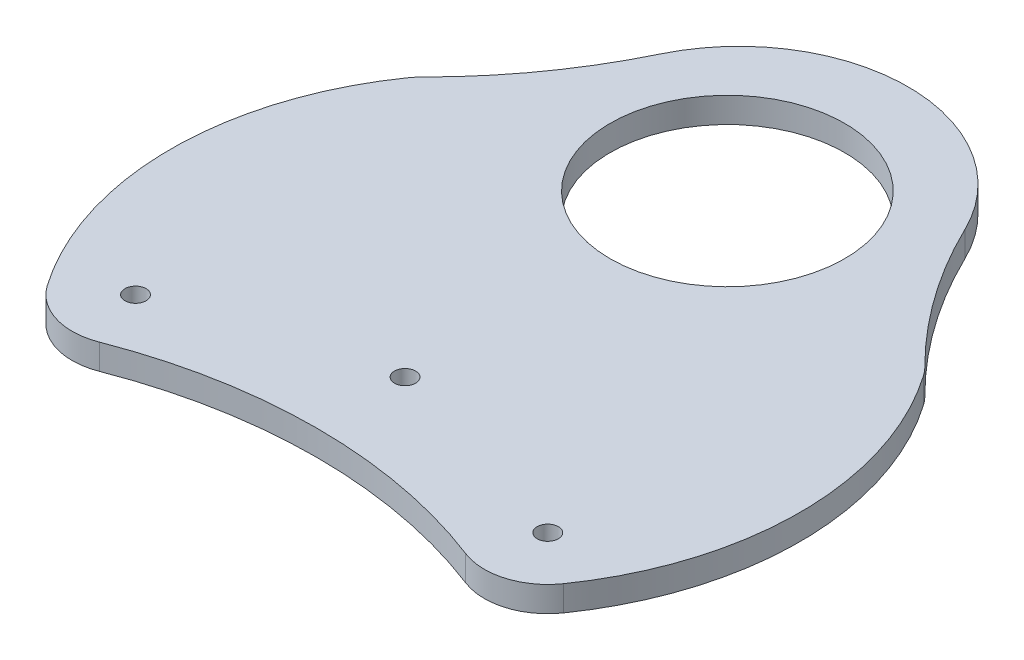
SolidWorks part; units mm, degrees
ref_plane "Front Plane" through (0, 0, 0) normal (0, 0, 1) x (1, 0, 0)
ref_plane "Top Plane" through (0, 0, 0) normal (0, 1, 0) x (1, 0, 0)
ref_plane "Right Plane" through (0, 0, 0) normal (1, 0, 0) x (0, 0, -1)
sketch "Sketch1" plane through (0, 0, 0) normal (0, 1, 0) x (1, 0, 0)
  line L0 (4.018, 0) -> (-26.2688, 0) construction
  line L1 (0, 8.2176) -> (0, -12.6559) construction
  line L2 (-24.3819, 14.3843) -> (-24.3819, -24.076) construction
  line L3 (24.3819, 10.5648) -> (24.3819, -19.0867) construction
  line L4 (-49.107, 13) -> (50.7773, 13) construction
  line L5 (-56.0514, -34) -> (44.643, -34) construction
  line L6 (-107.7128, -41.5) -> (7.8045, -41.5) construction
  line L7 (-98.3012, -26.5) -> (81.3557, -26.5) construction
  circle A0 centre (-24.3819, -34) radius 7.5 construction
  circle A1 centre (24.3819, -34) radius 7.5 construction
  circle A2 centre (-24.3819, 0) radius 7.5 construction
  circle A3 centre (24.3819, 0) radius 7.5 construction
  circle A4 centre (0, 13) radius 20 construction
  circle A5 centre (0, -17) radius 37.2234 construction
  circle A6 centre (-72.0281, 47.8131) radius 60 construction
  circle A7 centre (72.0281, 47.8131) radius 60 construction
  circle A8 centre (0, -96.9426) radius 60 construction
  arc A9 (-30.5342, -38.2896) -> (-30.5342, 4.2896) centre (0, -17) cw
  arc A10 (30.5342, -38.2896) -> (30.5342, 4.2896) centre (0, -17) ccw
  arc A11 (-29.676, 5.3126) -> (-18.007, 21.7033) centre (-72.0281, 47.8131) ccw
  arc A12 (18.007, 21.7033) -> (29.676, 5.3126) centre (72.0281, 47.8131) ccw
  arc A13 (-30.5342, -38.2896) -> (-21.6728, -40.9936) centre (-24.3819, -34) ccw
  arc A14 (30.5342, -38.2896) -> (21.6728, -40.9936) centre (24.3819, -34) cw
  arc A15 (29.676, 5.3126) -> (30.5342, 4.2896) centre (24.3819, 0) cw
  arc A16 (-18.007, 21.7033) -> (18.007, 21.7033) centre (0, 13) cw
  arc A17 (-29.676, 5.3126) -> (-30.5342, 4.2896) centre (-24.3819, 0) ccw
  arc A18 (-21.6728, -40.9936) -> (21.6728, -40.9936) centre (0, -96.9426) cw
  dimension "D6" = 15
  dimension "spine_width" = 40
  dimension "D1" = 120
  dimension "body_width" = 48.7639
  dimension "D2" = 24.3819
  dimension "shoulder_to_spine" = 13
  dimension "shoulder_to_foot" = 34
  dimension "centre_axis_height" = 15
extrude "Boss-Extrude1" add sketch "Sketch1" along normal blind 3
sketch "Sketch2" plane through (0, 3, 0) normal (0, 1, 0) x (1, 0, 0)
  line L0 (-200098.3012, -26.5) -> (200081.3557, -26.5) construction
  line L1 (0, 200008.2176) -> (0, -200012.6559) construction
  line L2 (-200098.3012, -26.5) -> (200081.3557, -26.5)
  line L3 (-38.0575, 13) -> (20.6031, 13) construction
  line L4 (0, 69.4786) -> (0, 57.8708) construction
  line L5 (13.8975, -26.5) -> (-27.3003, -26.5) construction
  line L6 (-33.0904, 11.63) -> (11.1046, 11.63) construction
  circle A0 centre (-24.3819, -34) radius 7.5 construction
  circle A1 centre (24.3819, -34) radius 7.5 construction
  circle A2 centre (24.3819, 0) radius 7.5 construction
  circle A3 centre (-24.3819, 0) radius 7.5 construction
  circle A4 centre (0, 13) radius 20 construction
  circle A5 centre (-24.3819, -34) radius 7.5 construction
  circle A6 centre (24.3819, -34) radius 7.5 construction
  circle A7 centre (24.3819, 0) radius 7.5 construction
  circle A8 centre (-24.3819, 0) radius 7.5 construction
  circle A9 centre (0, 13) radius 20 construction
  circle A10 centre (-24.3819, -34) radius 1.25
  circle A11 centre (24.3819, -34) radius 1.25
  circle A12 centre (0, -26.5) radius 1.25
  circle A13 centre (0, 11.63) radius 13.875
  dimension "D1" = 38.13
  dimension "elastic_hole" = 2.5
  dimension "D2" = 27.75
extrude "Cut-Extrude1" cut sketch "Sketch2" against normal through all
equation "\"D2@Sketch1\"=\"body_width@Sketch1\" / 2"
